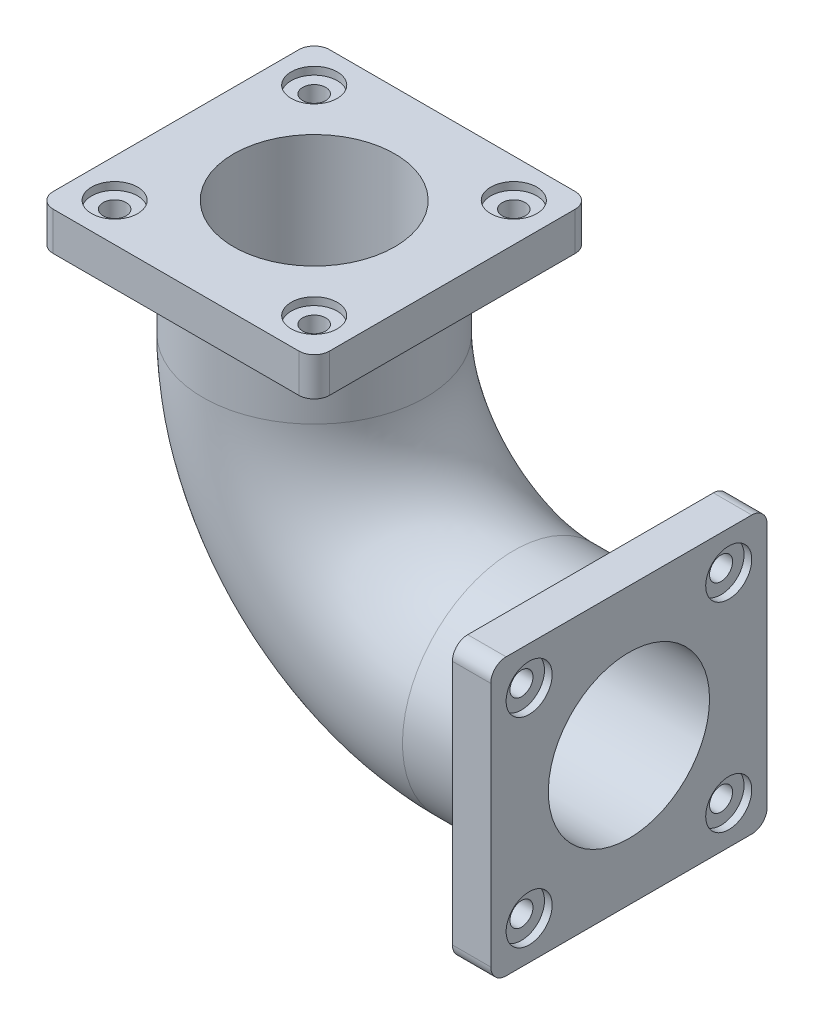
SolidWorks part; units mm, degrees
ref_plane "Front Plane" through (0, 0, 0) normal (0, 0, 1) x (1, 0, 0)
ref_plane "Top Plane" through (0, 0, 0) normal (0, 1, 0) x (1, 0, 0)
ref_plane "Right Plane" through (0, 0, 0) normal (1, 0, 0) x (0, 0, -1)
sketch "Sketch1" plane through (0, 0, 0) normal (0, 0, 1) x (1, 0, 0)
  line L0 (0, 0) -> (-15, 0)
  line L1 (-41, 26) -> (-41, 41)
  arc A0 (-15, 0) -> (-41, 26) centre (-15, 26) cw
sketch "Sketch2" plane through (0, 0, 0) normal (1, 0, 0) x (0, 0, -1)
  circle A0 centre (0, 0) radius 14.5
sweep "Sweep-Thin3" add profiles "Sketch2" path "Sketch1" parameters "D1"=4
sketch "Sketch9" plane through (0, 0, 0) normal (1, 0, 0) x (0, 0, -1)
  line L1 (-18, 18) -> (18, 18)
  line L2 (-18, 18) -> (-18, -18)
  line L3 (-18, -18) -> (18, -18)
  line L4 (18, 18) -> (18, -18)
  line L5 (-18, 18) -> (18, -18) construction
  line L6 (-18, -18) -> (18, 18) construction
  point P0 (0, 0)
  circle M4 centre (0, 0) radius 14.5
  dimension "D1" = 36
  dimension "D2" = 36
extrude "Boss-Extrude2" add sketch "Sketch9" against normal blind 5 contours L4 L1 L2 L3 M4
sketch "Sketch10" plane through (0, 0, 0) normal (1, 0, 0) x (0, 0, -1)
  line L1 (-13, 13) -> (13, 13) construction
  line L2 (-13, 13) -> (-13, -13) construction
  line L3 (-13, -13) -> (13, -13) construction
  line L4 (13, 13) -> (13, -13) construction
  line L5 (-13, 13) -> (13, -13) construction
  line L6 (-13, -13) -> (13, 13) construction
  circle A0 centre (-13, 13) radius 3
  point P0 (0, 0)
  dimension "D1" = 26
  dimension "D2" = 26
fillet "Fillet1" radius 2 1 edges at (-2.5, 18, 18)
fillet "Fillet2" radius 2 3 edges at (-2.5, 18, -18) (-2.5, -18, -18) (-2.5, -18, 18)
extrude "Cut-Extrude1" cut sketch "Sketch10" against normal blind 1 contours A0
sketch "Sketch13" plane through (-1, 0, 0) normal (1, 0, 0) x (0, 0, -1)
  circle A0 centre (-13, 13) radius 1.5
extrude "Cut-Extrude2" cut sketch "Sketch13" against normal up to next
pattern_circular "CirPattern1" count 4 over 360 about axis through (0, 0, 0) along (1, 0, 0) of "Cut-Extrude1", "Cut-Extrude2"
sketch "Sketch15" plane through (0, 41, 0) normal (0, 1, 0) x (1, 0, 0)
  line L1 (-59, 18) -> (-23, 18)
  line L2 (-59, 18) -> (-59, -18)
  line L3 (-59, -18) -> (-23, -18)
  line L4 (-23, 18) -> (-23, -18)
  line L5 (-59, 18) -> (-23, -18) construction
  line L6 (-59, -18) -> (-23, 18) construction
  point P0 (-41, 0)
  point P6 (0, 0)
  point P8 (0, 0)
  point P9 (0, 0)
  circle M6 centre (-41, 0) radius 14.5
  dimension "D1" = 36
  dimension "D2" = 36
extrude "Boss-Extrude6" add sketch "Sketch15" against normal blind 5 contours L4 L1 L2 L3 M6
fillet "Fillet3" radius 2 4 edges at (-59, 38.5, -18) (-59, 38.5, 18) (-23, 38.5, 18) (-23, 38.5, -18)
sketch "Sketch16" plane through (0, 41, 0) normal (0, 1, 0) x (1, 0, 0)
  line L0 (-41, 0) -> (-15, 0) construction
  line L1 (-54, 13) -> (-28, 13) construction
  line L2 (-54, 13) -> (-54, -13) construction
  line L3 (-54, -13) -> (-28, -13) construction
  line L4 (-28, 13) -> (-28, -13) construction
  line L5 (-54, 13) -> (-28, -13) construction
  line L6 (-54, -13) -> (-28, 13) construction
  circle A0 centre (-54, 13) radius 3
  point P0 (-41, 0)
  dimension "D1" = 26
  dimension "D2" = 26
extrude "Cut-Extrude4" cut sketch "Sketch16" against normal blind 1 contours A0
sketch "Sketch17" plane through (0, 40, 0) normal (0, 1, 0) x (1, 0, 0)
  circle A0 centre (-54, 13) radius 1.5
extrude "Cut-Extrude5" cut sketch "Sketch17" against normal up to next contours A0
pattern_circular "CirPattern2" count 4 over 360 about axis through (-41, 0, 0) along (0, 1, 0) of "Cut-Extrude5", "Cut-Extrude4"
